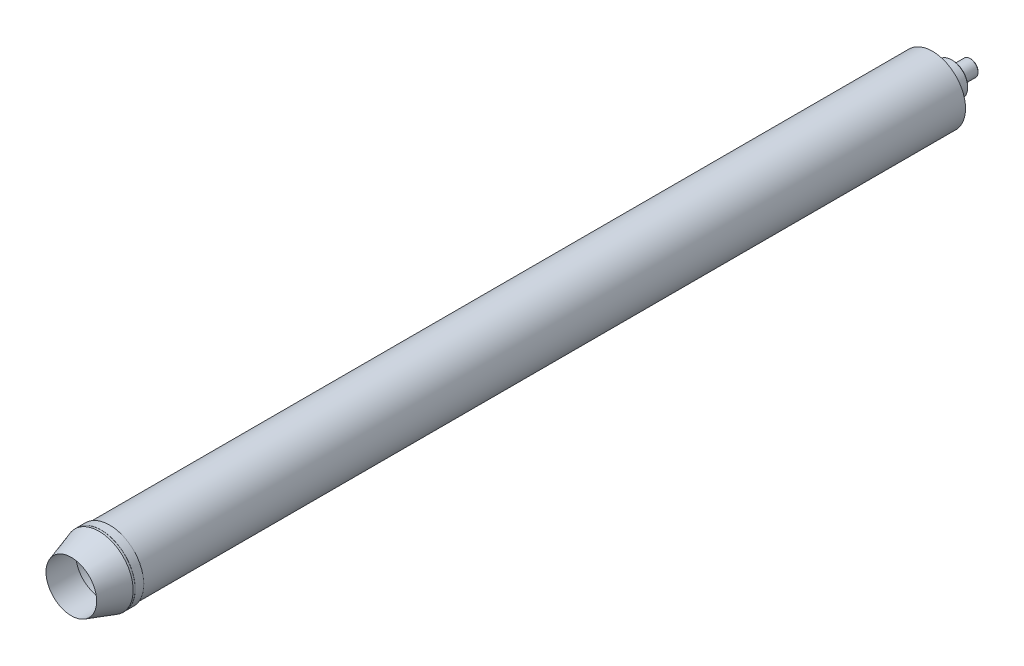
SolidWorks part; units mm, degrees
material "7075-T6 (SN)"
ref_plane "Front Plane" through (0, 0, 0) normal (0, 0, 1) x (1, 0, 0)
ref_plane "Top Plane" through (0, 0, 0) normal (0, 1, 0) x (1, 0, 0)
ref_plane "Right Plane" through (0, 0, 0) normal (1, 0, 0) x (0, 0, -1)
sketch "Sketch1" plane through (0, 0, 0) normal (0, 0, 1) x (1, 0, 0)
  circle A0 centre (0, 0) radius 49.2125
  circle A1 centre (0, 0) radius 47.625
  dimension "D1" = 98.425
  dimension "D2" = 1.5875
extrude "Boss-Extrude1" add sketch "Sketch1" along normal blind 1225.804
sketch "Sketch2" plane through (0, 0, 1225.804) normal (0, 0, 1) x (1, 0, 0)
  circle A0 centre (0, 0) radius 50.8
  circle A1 centre (0, 0) radius 47.625
  circle A2 centre (0, 0) radius 47.625 construction
  dimension "D1" = 101.6
extrude "Boss-Extrude2" add sketch "Sketch2" along normal blind 12.7
sketch "Sketch3" plane through (0, 0, 0) normal (0, 0, 1) x (1, 0, 0)
  circle A0 centre (0, 0) radius 47.625
extrude "Boss-Extrude3" add sketch "Sketch3" along normal blind 6.35
sketch "Sketch4" plane through (0, 0, 0) normal (0, 0, -1) x (-1, 0, 0)
  circle A0 centre (0, 0) radius 23.876
  dimension "D1" = 47.752
extrude "Boss-Extrude4" add sketch "Sketch4" along normal blind 29.845
sketch "Sketch5" plane through (0, 0, -29.845) normal (0, 0, -1) x (-1, 0, 0)
  circle A0 centre (0, 0) radius 11.938
  dimension "D1" = 23.876
extrude "Boss-Extrude5" add sketch "Sketch5" along normal blind 27.305
chamfer "Chamfer1" distance 1.27 angle 45 2 edges at (-11.938, 0, -57.15) (-23.876, 0, -29.845)
hole_wizard "3/8-16 Tapped Hole1" positions "Sketch7" profile "Sketch6" tap size "3/8-16" standard "ANSI Inch"
sketch "Sketch7" plane through (0, 0, -57.15) normal (0, 0, -1) x (-1, 0, 0)
  point P0 (0, 0)
sketch "Sketch6" plane through (0, 0, -57.15) normal (1, 0, 0) x (0, 1, 0)
  line L0 (0, 0) -> (0, 29.3722)
  line L1 (0, 29.3722) -> (3.9687, 26.9875)
  line L2 (3.9687, 26.9875) -> (3.9687, 0)
  line L5 (3.9687, 0) -> (0, 0)
  line L10 (0, 29.3722) -> (-3.9688, 26.9875) construction
  line L11 (0, -6.35) -> (0, 107.95) construction
  dimension "Tap Drill Dia." = 7.9375
  dimension "Tap Drill Depth" = 26.9875
  dimension "Drill Angle" = 118
cosmetic thread "Hole Thread1" parameters "D1"=19.05, "D2"=9.525
sketch "Sketch8" plane through (0, 0, 0) normal (0, 0, -1) x (-1, 0, 0)
  circle A0 centre (0, 0) radius 23.876
  circle A1 centre (0, 0) radius 46.0375
  circle A2 centre (0, 0) radius 49.2125 construction
  circle A3 centre (0, 0) radius 23.876 construction
  dimension "D1" = 3.175
extrude "Cut-Extrude1" cut sketch "Sketch8" against normal blind 3.175
sketch "Sketch9" plane through (0, 0, 0) normal (0, 1, 0) x (1, 0, 0)
  line L0 (-50.8, -1238.758) -> (-50.8, -1241.679)
  line L1 (-50.8, -1241.679) -> (-37.719, -1282.954)
  line L2 (-37.719, -1282.954) -> (-37.719, -1238.504)
  line L3 (-50.8, -1238.504) -> (50.8, -1238.504) construction
  line L4 (-37.719, -1238.504) -> (-50.546, -1238.504)
  line L5 (0, -1238.504) -> (0, -1303.0674) construction
  line L6 (-50.546, -1238.504) -> (-50.546, -1238.758)
  line L7 (-50.546, -1238.758) -> (-50.8, -1238.758)
  dimension "D1" = 37.719
  dimension "D2" = 44.45
  dimension "D3" = 0.254
  dimension "D4" = 0.254
  dimension "D5" = 2.921
revolve "Revolve1" add sketch "Sketch9" angle 360 about L5
